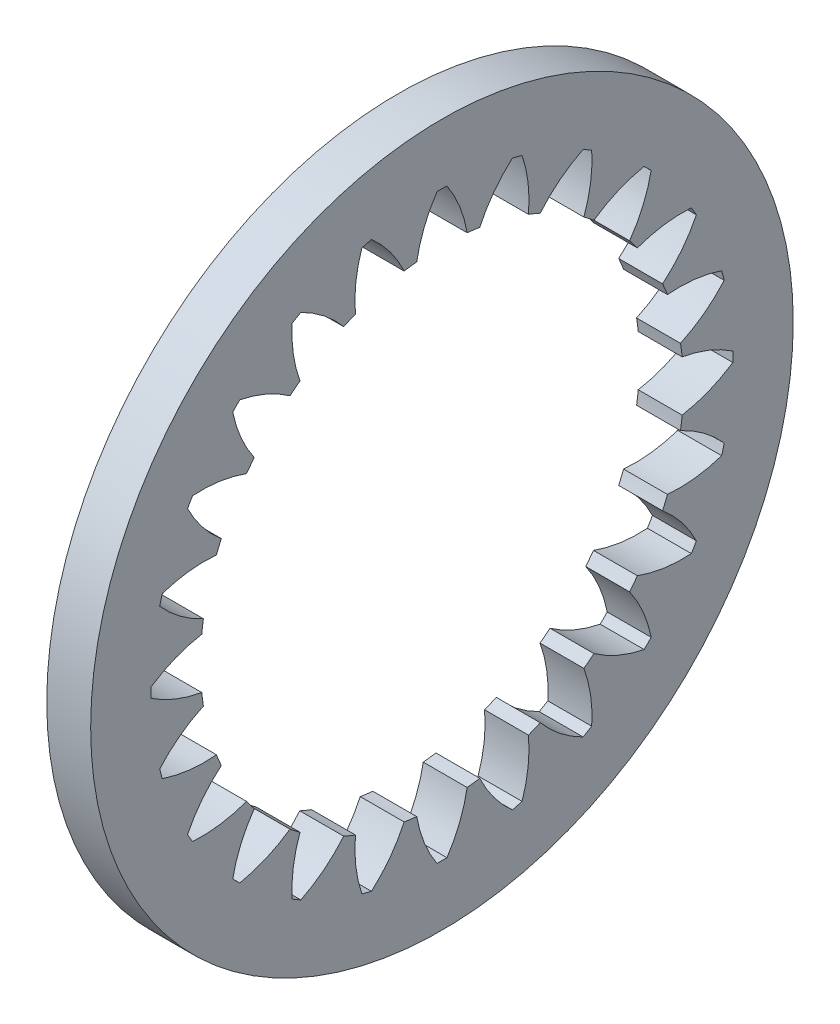
SolidWorks part; units mm, degrees
ref_plane "Plane1" through (0, 0, 0) normal (0, 0, 1) x (1, 0, 0)
ref_plane "Plane2" through (0, 0, 0) normal (0, 1, 0) x (1, 0, 0)
ref_plane "Plane3" through (0, 0, 0) normal (1, 0, 0) x (0, 0, -1)
other "Configuration Table"
sketch "HoldingSke" plane through (0, 0, 0) normal (0, 1, 0) x (1, 0, 0)
  line L0 (0, 0) -> (-17.6427, -100.0565)
  line L1 (-15, 0) -> (100, 0) construction
  line L2 (0, 0) -> (-2.1039, 2.3779)
  line L3 (0, 0) -> (-11.863, 4.5341)
  line L4 (0, 0) -> (7.8894, 3.5126)
  line L5 (0, 0) -> (-23.7986, -8.8762)
  line L6 (0, 0) -> (-10.5278, -7.1032)
  line L7 (-2.1039, 2.3779) -> (3.3635, 27.1825)
  line L8 (-76.2, 54.61) -> (-54.61, 54.61)
  line L9 (-67.7845, 28.3722) -> (-49.3413, 33.142)
  line L10 (-76.2, 71.12) -> (104.1128, 71.12)
  line L11 (0, 0) -> (-12.7, 0)
  line L12 (-76.2, 101.6) -> (-75.9714, 101.6)
  line L13 (24.9733, 27.94) -> (52.9518, 28.4284)
  line L14 (24.9733, 27.94) -> (24.9746, 27.94)
  line L15 (24.9733, 27.94) -> (100.4006, 29.5858)
  circle A0 centre (0, 0) radius 101.6
  circle A1 centre (0, 0) radius 12.7
  circle A2 centre (0, 0) radius 12.7
  dimension "MHD" = 25.4
  dimension "Hub_dia" = 25.4
  dimension "Diameter" = 203.2
  dimension "Num_teeth" = 24
  dimension "Pitch" = 101.6
  dimension "Overall_len" = 25.4
  dimension "Show_teeth" = 100
  dimension "Thickness" = 12.7
  dimension "OAL" = 25.4001
  dimension "T_dim" = 21.59
  dimension "Ap" = 14.5
  dimension "H" = 19.05
  dimension "Pitch_radius" = 180.3128
  dimension "Width" = 12.7
  dimension "Backlash" = 0.2286
  dimension "Addendum_fac" = 1
  dimension "Dedendum_fac" = 1.25
  dimension "Clearance_fac" = 0.25
  dimension "Dedendum_add" = 0.0013
sketch "BasProSke" plane through (0, 0, 0) normal (0, 1, 0) x (1, 0, 0)
  line L0 (-10, 0) -> (60, 0) construction
  line L1 (0, 69.85) -> (0, 101.6)
  line L2 (0, 69.85) -> (12.7, 69.85)
  line L3 (12.7, 69.85) -> (12.7, 101.6)
  line L4 (12.7, 101.6) -> (0, 101.6)
  dimension "Diameter" = 203.2
  dimension "Thickness" = 12.7
  dimension "Inside_diameter" = 139.7
revolve "Base-Revolve" add sketch "BasProSke" angle 360 about L0
sketch "TooCutSke" plane through (0, 0, 0) normal (1, 0, 0) x (0, 0, -1)
  line L3 (5.5552, 75.9972) -> (5.5552, 53.6633) construction
  line L4 (0, 0) -> (0, 59.563) construction
  line L5 (0, 0) -> (-8.9185, 67.7429) construction
  line L6 (-30.2541, 62.9855) -> (28.8527, 70.767) construction
  circle A0 centre (0, 0) radius 76.2 construction
  circle A1 centre (0, 0) radius 84.1388 construction
  circle A2 centre (0, 0) radius 66.3956 construction
  circle A3 centre (0, 0) radius 69.8246 construction
  arc A4 (7.2948, 69.4425) -> (1.4425, 84.1264) centre (-30.2541, 62.9855) ccw
  arc A5 (7.2948, 69.4425) -> (-7.2948, 69.4425) centre (0, 0) ccw
  arc A6 (1.4425, 84.1264) -> (-1.4425, 84.1264) centre (0, 0) ccw
  arc A7 (-1.4425, 84.1264) -> (-7.2948, 69.4425) centre (30.2541, 62.9855) ccw
  dimension "Pitch_dia" = 152.4
  dimension "Base_dia" = 132.7911
  dimension "Root_dia" = 168.2775
  dimension "Overcut_dia" = 139.6492
  dimension "Flank_rad" = 38.1
  dimension "Half_ang" = 7.5
  dimension "Half_CT" = 5.5552
extrude "ToothCut" cut sketch "TooCutSke" along normal through all
fillet "Breaks" [suppressed] radius 0.635
fillet "RootFillets" [suppressed] radius 1.5888
pattern_circular "TeethCuts" count 24 every 15 about axis through (-10, 0, 0) along (1, 0, 0) of "RootFillets", "Breaks", "ToothCut"
equation "' \"Pitch@HoldingSke\" = 4"
equation "' \"Num_teeth@HoldingSke\" = 24"
equation "' \"Ap@HoldingSke\" =  14.5"
equation "' \"Ap@HoldingSke\" = 14.5"
equation "' \"Width@HoldingSke\" = 0.5"
equation "' \"Diameter@HoldingSke\" = 8"
equation "' \"Show_teeth@HoldingSke\" = 100"
equation "' \"Backlash@HoldingSke\" = 0.009"
equation "' \"Addendum_fac@HoldingSke\" = 1.0"
equation "' \"Dedendum_fac@HoldingSke\" = 1.25"
equation "' \"Dedendum_add@HoldingSke\" = 0.00005"
equation "' \"Clearance_fac@HoldingSke\" = 0.25"
equation "\"Overcut_dia@TooCutSke\" = (\"Num_teeth@HoldingSke\" - 2 * \"Addendum_fac@HoldingSke\") / \"Pitch@HoldingSke\" - 0.002"
equation "\"Pitch_dia@TooCutSke\" = \"Num_teeth@HoldingSke\" / \"Pitch@HoldingSke\""
equation "\"Base_dia@TooCutSke\" = \"Num_teeth@HoldingSke\" / \"Pitch@HoldingSke\" * cos((\"Ap@HoldingSke\"  * 3.14159265 / 180)) * 0.90"
equation "\"Root_dia@TooCutSke\" = \"Num_teeth@HoldingSke\"  / \"Pitch@HoldingSke\" + 2 *  \"Dedendum_fac@HoldingSke\"/ \"Pitch@HoldingSke\" + \"Dedendum_add@HoldingSke\" * 2"
equation "\"Half_ang@TooCutSke\" = 180 / \"Num_teeth@HoldingSke\""
equation "\"Half_CT@TooCutSke\" = \"Num_teeth@HoldingSke\" / \"Pitch@HoldingSke\" * sin((3.14159265 / 2 / \"Num_teeth@HoldingSke\")) / 2 + 10 * \"Backlash@HoldingSke\" / 4"
equation "\"Flank_rad@TooCutSke\" = \"Num_teeth@HoldingSke\" / \"Pitch@HoldingSke\" / 4"
equation "\"Radius@RootFillets\"= \"Clearance_fac@HoldingSke\" / \"Pitch@HoldingSke\" + \"Dedendum_add@HoldingSke\""
equation "\"Break_rad@Breaks\" = 0.02 / \"Pitch@HoldingSke\" * 5"
equation "\"Num_teeth@TeethCuts\" = int( \"Show_teeth@HoldingSke\" ) + 1"
equation "\"Num_teeth@TeethCuts\" = ((sgn( \"Num_teeth@TeethCuts\" - \"Num_teeth@HoldingSke\" )-1)*( \"Num_teeth@TeethCuts\" - \"Num_teeth@HoldingSke\" ))/-2+ \"Num_teeth@HoldingSke\""
equation "\"Num_teeth@TeethCuts\" = ((sgn( \"Num_teeth@TeethCuts\" - 2.0)+1)*( \"Num_teeth@TeethCuts\" - 2.0))/2 +2.0"
equation "\"Angle@TeethCuts\" = 360.0 / \"Num_teeth@HoldingSke\""
equation "\"Diameter@BasProSke\" = \"Num_teeth@HoldingSke\"  / \"Pitch@HoldingSke\" + 2 *  \"Dedendum_fac@HoldingSke\"/ \"Pitch@HoldingSke\" + \"Dedendum_add@HoldingSke\" * 2 + 0.002"
equation "\"Diameter@BasProSke\" = ((sgn( \"Diameter@BasProSke\"  - \"Diameter@HoldingSke\" )+1)*( \"Diameter@BasProSke\"  - \"Diameter@HoldingSke\" ))/2 + \"Diameter@HoldingSke\""
equation "\"Inside_diameter@BasProSke\" =  (\"Num_teeth@HoldingSke\" - 2 * \"Addendum_fac@HoldingSke\") / \"Pitch@HoldingSke\" "
equation "\"Thickness@BasProSke\"  = \"Width@HoldingSke\""
